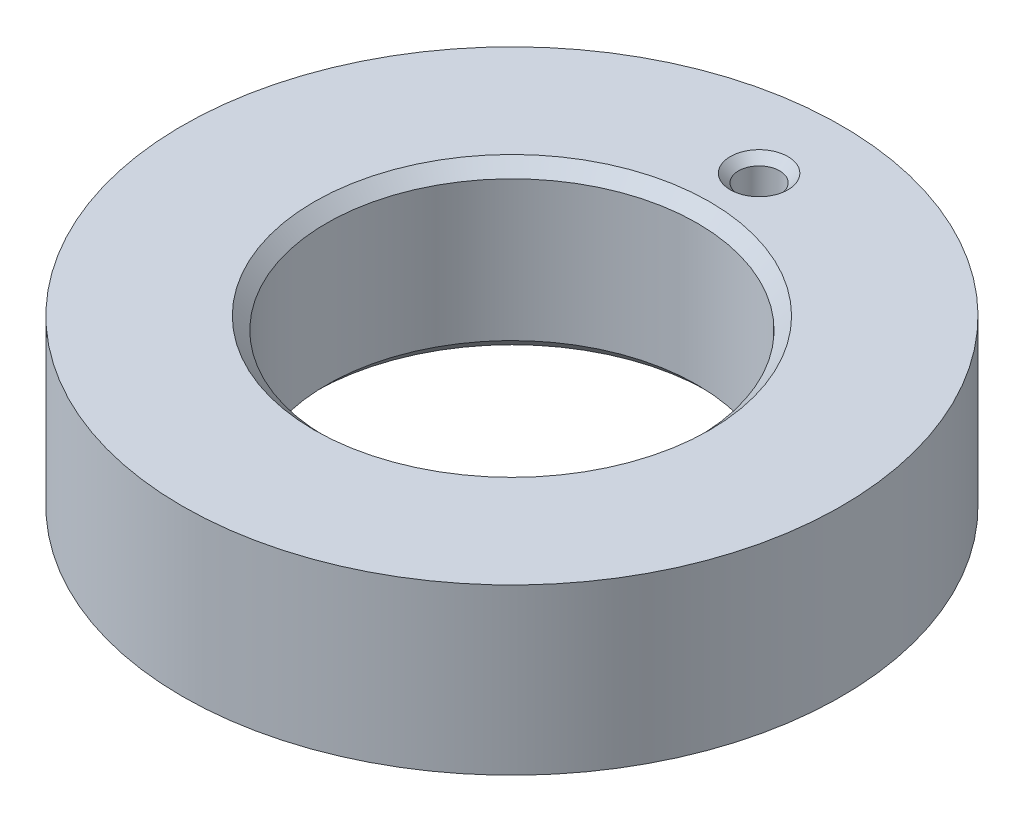
SolidWorks part; units mm, degrees
ref_plane "Спереди" through (0, 0, 0) normal (0, 0, 1) x (1, 0, 0)
ref_plane "Сверху" through (0, 0, 0) normal (0, 1, 0) x (1, 0, 0)
ref_plane "Справа" through (0, 0, 0) normal (1, 0, 0) x (0, 0, -1)
sketch "Эскиз1" plane through (0, 0, 0) normal (0, 1, 0) x (1, 0, 0)
  circle A0 centre (0, 0) radius 40
  dimension "D1" = 80
extrude "Бобышка-Вытянуть1" add sketch "Эскиз1" along normal blind 20 contours A0
sketch "Эскиз2" plane through (0, 20, 0) normal (0, 1, 0) x (1, 0, 0)
  circle A0 centre (0, 0) radius 22.5
  dimension "D2" = 45
extrude "Вырез-Вытянуть1" cut sketch "Эскиз2" against normal through all
chamfer "Фаска1" distance 1.5 angle 45 2 edges at (0, 20, 22.5) (0, 0, 22.5)
sketch "Эскиз3" plane through (0, 0, 0) normal (0, -1, 0) x (1, 0, 0)
  circle A0 centre (0, -30) radius 2.5
  circle A1 centre (0, 0) radius 30 construction
  dimension "D1" = 5
  dimension "D2" = 60
extrude "ОтверстиеБоковое" cut sketch "Эскиз3" against normal through all
chamfer "Фаска2" distance 1 angle 45 2 edges at (0, 20, -32.5) (0, 0, -32.5)
